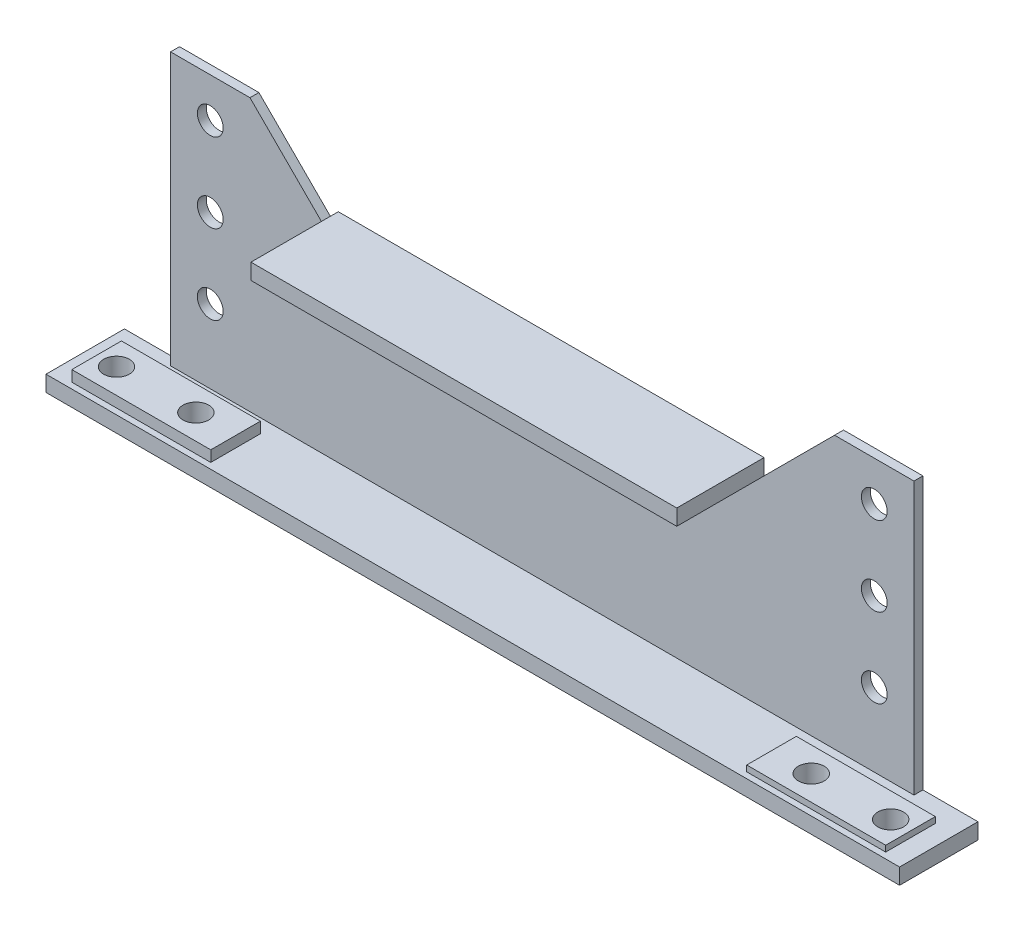
SolidWorks part; units mm, degrees
ref_plane "前视基准面" through (0, 0, 0) normal (0, 0, 1) x (1, 0, 0)
ref_plane "上视基准面" through (0, 0, 0) normal (0, 1, 0) x (1, 0, 0)
ref_plane "右视基准面" through (0, 0, 0) normal (1, 0, 0) x (0, 0, -1)
sketch "草图1" plane through (0, 0, 0) normal (0, 0, 1) x (1, 0, 0)
  line L0 (-1000, 0) -> (49000, 0) construction
  line L1 (0, -1000) -> (0, 49000) construction
  line L2 (0, 0) -> (860, 0)
  line L3 (55.5, -562.2618) -> (55.5, 49437.7382) construction
  line L4 (-1038.7035, 16) -> (48961.2965, 16) construction
  line L5 (860, -1000) -> (860, 49000) construction
  line L6 (804.5, -950.8793) -> (804.5, 49049.1207) construction
  line L7 (-663.1285, 290) -> (49336.8715, 290) construction
  line L8 (-660.6051, 210) -> (49339.3949, 210) construction
  line L9 (0, 0) -> (0, 16)
  line L10 (0, 16) -> (55.5, 16)
  line L11 (860, 0) -> (860, 16)
  line L12 (860, 16) -> (804.5, 16)
  line L13 (55.5, 290) -> (135.5, 290)
  line L14 (804.5, 290) -> (724.5, 290)
  line L15 (55.5, 16) -> (55.5, 290)
  line L16 (804.5, 16) -> (804.5, 290)
  line L17 (135.5, 290) -> (215.5, 210) construction
  line L18 (724.5, 290) -> (644.5, 210) construction
  line L19 (135.5, 290) -> (215.5, 210)
  line L20 (724.5, 290) -> (644.5, 210)
  line L21 (215.5, 210) -> (215.5, 226)
  line L22 (95.5, -794.5532) -> (95.5, 49205.4468) construction
  line L23 (764.5, -804.9005) -> (764.5, 49195.0995) construction
  line L24 (-871.0333, 90) -> (49128.9667, 90) construction
  line L25 (-452.5392, 170) -> (49547.4608, 170) construction
  line L26 (-439.8924, 250) -> (49560.1076, 250) construction
  line L27 (644.5, 210) -> (644.5, 226)
  line L28 (215.5, 226) -> (644.5, 226)
  circle A0 centre (95.5, 90) radius 13
  circle A1 centre (95.5, 170) radius 13
  circle A2 centre (95.5, 250) radius 13
  circle A3 centre (764.5, 90) radius 13
  circle A4 centre (764.5, 170) radius 13
  circle A5 centre (764.5, 250) radius 13
  point P10 (0, 16)
  point P15 (860, 16)
  point P17 (804.5, 16)
  point P18 (55.5, 16)
  point P22 (55.5, 290)
  point P28 (804.5, 290)
  point P44 (764.5, 90)
  point P46 (764.5, 170)
  point P47 (764.5, 250)
  point P48 (95.5, 90)
  point P49 (95.5, 170)
  point P50 (95.5, 250)
  dimension "D17" = 26
  dimension "D18" = 26
  dimension "D19" = 26
  dimension "D20" = 26
  dimension "D21" = 26
  dimension "D22" = 26
  dimension "D1" = 860
  dimension "D2" = 55.5
  dimension "D3" = 16
  dimension "D4" = 860
  dimension "D5" = 55.5
  dimension "D6" = 290
  dimension "D7" = 210
  dimension "D8" = 80
  dimension "D9" = 80
  dimension "D10" = 45
  dimension "D11" = 45
  dimension "D12" = 40
  dimension "D13" = 40
  dimension "D14" = 90
  dimension "D15" = 80
  dimension "D16" = 80
  dimension "D23" = 16
  dimension "D24" = 16
extrude "凸台-拉伸2" add sketch "草图1" along normal blind 9
sketch "草图3" plane through (0, 0, 9) normal (0, 0, 1) x (1, 0, 0)
  line L0 (0, 0) -> (860, 0)
  line L1 (0, 0) -> (0, 16)
  line L2 (0, 16) -> (860, 16)
  line L3 (860, 16) -> (860, 0)
extrude "凸台-拉伸3" add sketch "草图3" along normal blind 70
sketch "草图4" plane through (0, 16, 0) normal (0, 1, 0) x (1, 0, 0)
  line L0 (-1008.5696, -48) -> (48991.4304, -48) construction
  line L1 (55.5, 0) -> (0, 0) construction
  line L3 (20, -1060.4184) -> (20, 48939.5816) construction
  line L4 (0, -79) -> (0, 0) construction
  line L5 (-980, -23) -> (49020, -23) construction
  line L7 (20, -23) -> (160, -23)
  line L8 (20, -23) -> (20, -73)
  line L9 (20, -73) -> (160, -73)
  line L10 (160, -23) -> (160, -73)
  point P9 (20, -23)
  dimension "D1" = 48
  dimension "D2" = 20
  dimension "D3" = 25
  dimension "D4" = 140
  dimension "D5" = 50
extrude "凸台-拉伸5" add sketch "草图4" along normal blind 11
sketch "草图5" plane through (0, 27, 0) normal (0, 1, 0) x (1, 0, 0)
  line L0 (-938.461, -48) -> (49061.539, -48) construction
  line L1 (55.5, 0) -> (0, 0) construction
  line L2 (40, -1048) -> (40, 48952) construction
  line L3 (0, -79) -> (0, 0) construction
  circle A0 centre (40, -48) radius 13
  point P10 (40, -48)
  dimension "D3" = 26
  dimension "D1" = 48
  dimension "D2" = 40
extrude "切除-拉伸2" cut sketch "草图5" against normal through all
pattern_linear "阵列(线性)1" count 2 spacing 80 along (1, 0, 0) of "切除-拉伸2"
sketch "草图6" plane through (0, 16, 0) normal (0, 1, 0) x (1, 0, 0)
  line L0 (840, -1040.034) -> (840, 48959.966) construction
  line L1 (860, -79) -> (860, 0) construction
  line L2 (-442.9077, -23) -> (49557.0923, -23) construction
  line L3 (860, 0) -> (804.5, 0) construction
  line L5 (840, -23) -> (700, -23)
  line L6 (840, -23) -> (840, -73)
  line L7 (840, -73) -> (700, -73)
  line L8 (700, -23) -> (700, -73)
  point P8 (840, -23)
  dimension "D1" = 20
  dimension "D2" = 23
  dimension "D3" = 140
  dimension "D4" = 50
extrude "凸台-拉伸6" add sketch "草图6" along normal blind 6
sketch "草图7" plane through (0, 22, 0) normal (0, 1, 0) x (1, 0, 0)
  line L0 (-220.763, -48) -> (49779.237, -48) construction
  line L1 (860, 0) -> (804.5, 0) construction
  line L2 (820, -1054.986) -> (820, 48945.014) construction
  line L3 (860, -79) -> (860, 0) construction
  circle A0 centre (820, -48) radius 13
  point P8 (820, -48)
  dimension "D3" = 26
  dimension "D1" = 48
  dimension "D2" = 40
extrude "切除-拉伸3" cut sketch "草图7" against normal through all
pattern_linear "阵列(线性)2" count 2 spacing 80 along (-1, 0, 0) of "切除-拉伸3"
sketch "草图10" plane through (0, 0, 9) normal (0, 0, 1) x (1, 0, 0)
  line L1 (215.5, 226) -> (644.5, 226)
  line L2 (215.5, 226) -> (215.5, 210)
  line L3 (215.5, 210) -> (644.5, 210)
  line L4 (644.5, 226) -> (644.5, 210)
  dimension "D1" = 429
  dimension "D2" = 16
extrude "凸台-拉伸8" add sketch "草图10" along normal blind 79
